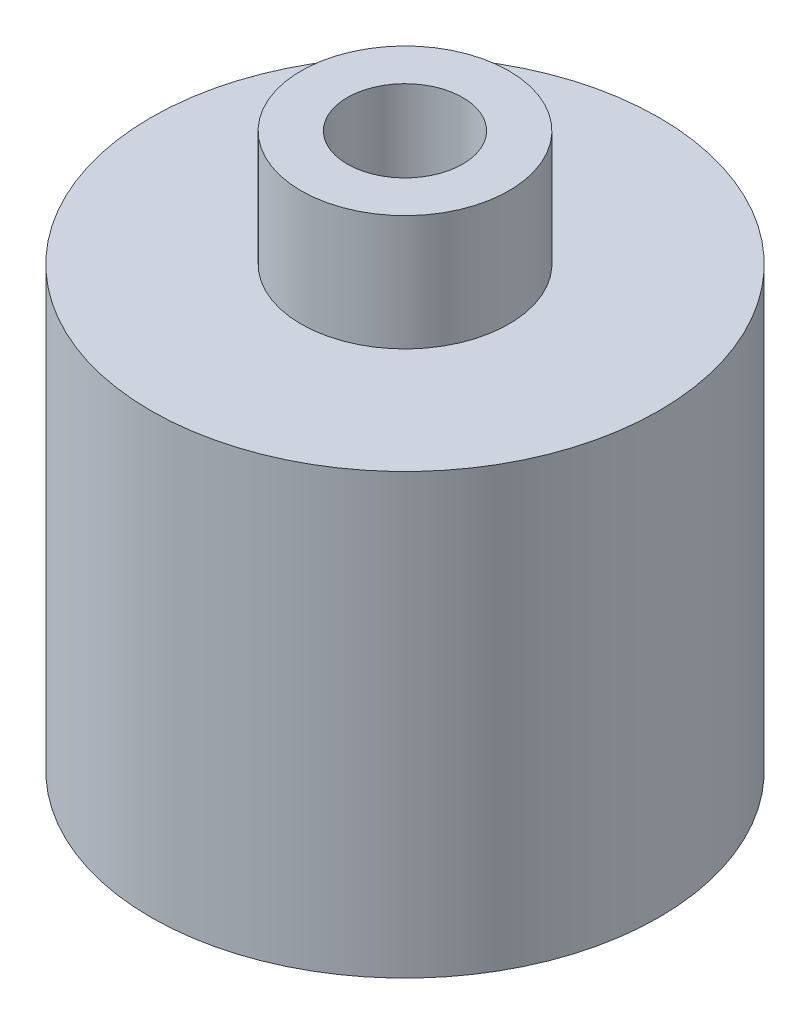
SolidWorks part; units mm, degrees
ref_plane "前视基准面" through (0, 0, 0) normal (0, 0, 1) x (1, 0, 0)
ref_plane "上视基准面" through (0, 0, 0) normal (0, 1, 0) x (1, 0, 0)
ref_plane "右视基准面" through (0, 0, 0) normal (1, 0, 0) x (0, 0, -1)
other "Configuration Table"
sketch "Sketch1" plane through (0, 0, 0) normal (0, 1, 0) x (1, 0, 0)
  circle A0 centre (0, 0) radius 11
  circle A1 centre (0, 0) radius 2.5
extrude "Boss-Extrude1" add sketch "Sketch1" along normal blind 19
sketch "Sketch2" plane through (0, 19, 0) normal (0, 1, 0) x (1, 0, 0)
  circle A0 centre (0, 0) radius 4.5
  circle A1 centre (0, 0) radius 2.5
extrude "Boss-Extrude4" add sketch "Sketch2" along normal blind 5
